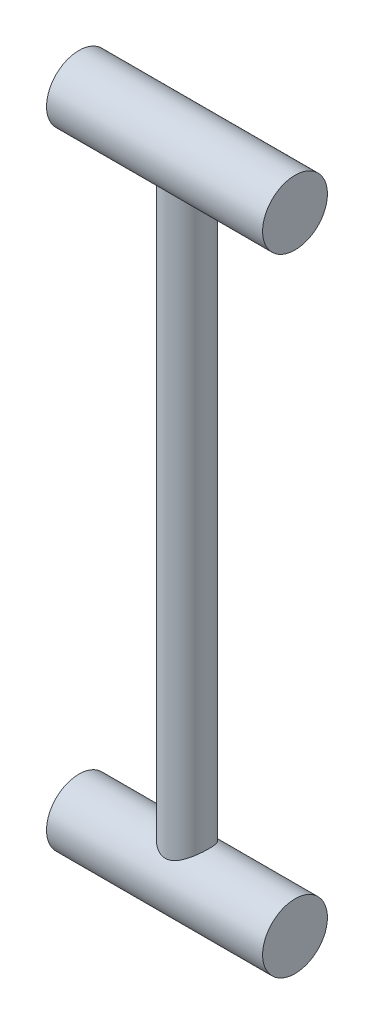
SolidWorks part; units mm, degrees
ref_plane "Front Plane" through (0, 0, 0) normal (0, 0, 1) x (1, 0, 0)
ref_plane "Top Plane" through (0, 0, 0) normal (0, 1, 0) x (1, 0, 0)
ref_plane "Right Plane" through (0, 0, 0) normal (1, 0, 0) x (0, 0, -1)
sketch "Sketch1" plane through (0, 0, 0) normal (0, 0, 1) x (1, 0, 0)
  line L0 (0, 145) -> (0, -145) construction
  line L1 (0, 145) -> (-10, 145)
  line L2 (-10, 145) -> (-10, -145)
  line L3 (-10, -145) -> (0, -145)
  line L4 (0, -145) -> (0, 145)
  point P4 (0, 0)
  dimension "D1" = 290
  dimension "D2" = 10
revolve "Revolve1" add sketch "Sketch1" angle 360 about L0
sketch "Sketch2" plane through (0, 0, 0) normal (1, 0, 0) x (0, 0, -1)
  line L0 (10, 145) -> (-10, 145) construction
  circle A0 centre (0, 145) radius 15
  dimension "D1" = 30
extrude "Boss-Extrude1" add sketch "Sketch2" along normal mid plane 100
mirror "Mirror1" about plane through (0, 0, 0) normal (0, 1, 0) of "Boss-Extrude1"
